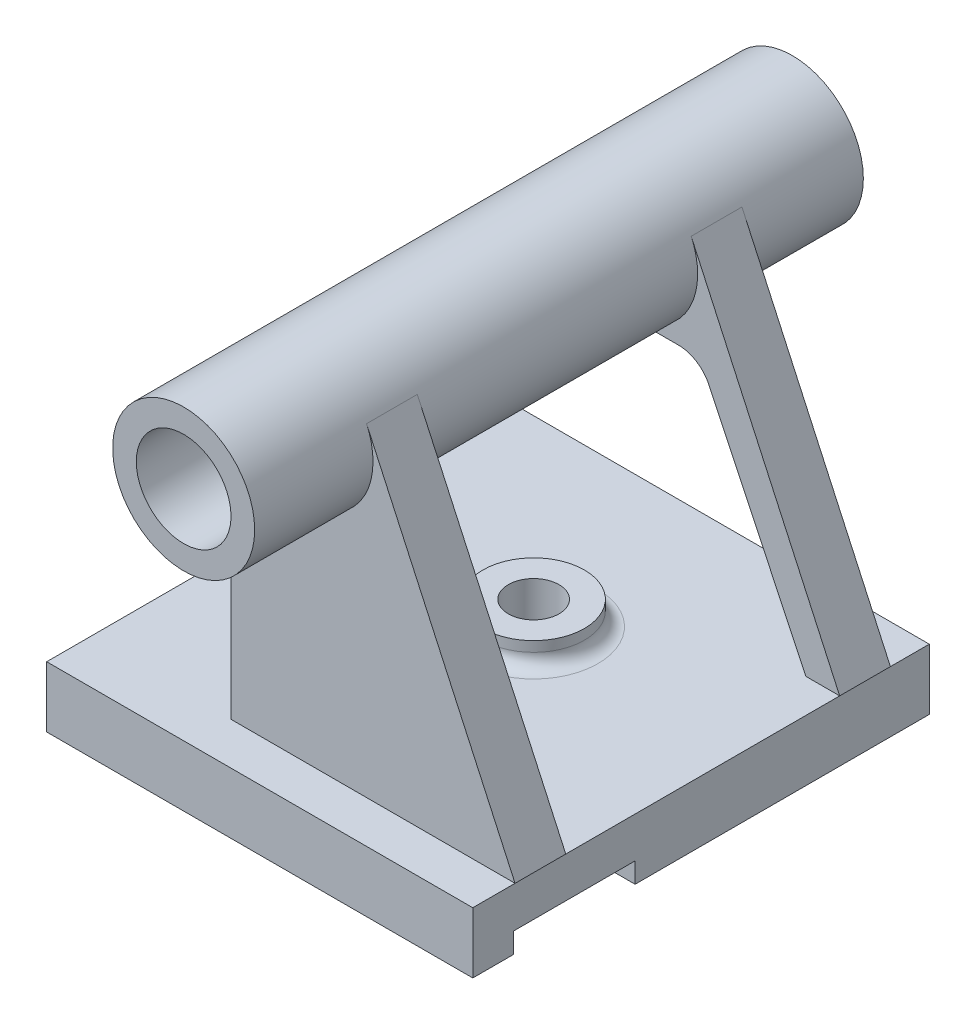
SolidWorks part; units mm, degrees
ref_plane "Front Plane" through (0, 0, 0) normal (0, 0, 1) x (1, 0, 0)
ref_plane "Top Plane" through (0, 0, 0) normal (0, 1, 0) x (1, 0, 0)
ref_plane "Right Plane" through (0, 0, 0) normal (1, 0, 0) x (0, 0, -1)
sketch "Sketch1" plane through (0, 0, 0) normal (0, 0, 1) x (1, 0, 0)
  circle A0 centre (0, 0) radius 21
  circle A1 centre (0, 0) radius 14
  dimension "D1" = 28
  dimension "D2" = 42
extrude "Boss-Extrude1" add sketch "Sketch1" along normal blind 180
ref_plane "Plane1" through (0, 0, 90) normal (0, 0, -1) x (-1, 0, 0)
sketch "Sketch3" plane through (0, 0, 90) normal (0, 0, -1) x (-1, 0, 0)
  line L0 (0, 0) -> (0, -96) construction
  line L2 (-63, -87) -> (63, -87)
  line L3 (-63, -87) -> (-63, -105)
  line L4 (-63, -105) -> (63, -105)
  line L5 (63, -87) -> (63, -105)
  line L6 (-63, -87) -> (63, -105) construction
  line L7 (-63, -105) -> (63, -87) construction
  dimension "D1" = 96
  dimension "D2" = 18
  dimension "D3" = 63
extrude "Boss-Extrude3" add sketch "Sketch3" along normal mid plane 135 separate body
sketch "Sketch4" plane through (63, 0, 0) normal (1, 0, 0) x (0, 0, -1)
  line L0 (-22.5, -105) -> (-157.5, -105) construction
  line L1 (-145.5, -105) -> (-109.5, -105)
  line L2 (-145.5, -105) -> (-145.5, -99)
  line L3 (-145.5, -99) -> (-109.5, -99)
  line L4 (-109.5, -105) -> (-109.5, -99)
  line L5 (-157.5, -87) -> (-157.5, -105) construction
  point P6 (0, 0)
  point P8 (-157.5, -105)
  dimension "D1" = 6
  dimension "D2" = 12
  dimension "D3" = 36
extrude "Cut-Extrude1" cut sketch "Sketch4" against normal blind 135
sketch "Sketch5" plane through (0, -87, 0) normal (0, 1, 0) x (1, 0, 0)
  line L0 (63, -76.5) -> (-63, -76.5) construction
  line L1 (63, -22.5) -> (63, -157.5) construction
  line L2 (-63, -22.5) -> (-63, -157.5) construction
  line L3 (0, -22.5) -> (0, -157.5) construction
  line L4 (-63, -22.5) -> (63, -22.5) construction
  line L5 (-63, -157.5) -> (63, -157.5) construction
  circle A0 centre (0, -76.5) radius 15
  circle A1 centre (0, -76.5) radius 7.5
  dimension "D2" = 15
  dimension "D3" = 30
  dimension "D1" = 81
extrude "Boss-Extrude4" add sketch "Sketch5" along normal blind 7
fillet "Fillet1" radius 4 1 edges at (0, -87, 61.5)
ref_plane "Plane2" through (0, 0, 145) normal (0, 0, 1) x (1, 0, 0)
sketch "Sketch6" plane through (0, 0, 145) normal (0, 0, 1) x (1, 0, 0)
  line L0 (-21, 0) -> (-21, -87)
  line L1 (-63, -87) -> (63, -87) construction
  line L2 (19.0885, 8.7538) -> (63, -87)
  line L3 (-21, -87) -> (63, -87)
  line L4 (63, -87) -> (63, -105) construction
  circle A0 centre (0, 0) radius 21 construction
  arc A1 (-21, 0) -> (19.0885, 8.7538) centre (0, 0) ccw
extrude "Boss-Extrude5" add sketch "Sketch6" against normal blind 15
ref_plane "Plane3" through (0, 0, 49) normal (0, 0, -1) x (-1, 0, 0)
sketch "Sketch8" plane through (0, 0, 49) normal (0, 0, -1) x (-1, 0, 0)
  line L0 (0, -21) -> (-15.3174, -21)
  line L1 (-24.3495, -26.708) -> (-53, -87)
  line L2 (63, -87) -> (-63, -87) construction
  line L3 (-19.0885, 8.7538) -> (-63, -87)
  line L4 (-63, -87) -> (-63, -105) construction
  line L5 (-63, -87) -> (-53, -87)
  arc A0 (-19.0885, 8.7538) -> (21, 0) centre (0, 0) ccw construction
  circle A1 centre (0, 0) radius 21 construction
  arc A2 (-15.3174, -21) -> (-24.3495, -26.708) centre (-15.3174, -31) ccw
  arc A3 (0, -21) -> (-19.0885, 8.7538) centre (0, 0) cw
  dimension "D1" = 10
  dimension "D2" = 10
  dimension "D3" = 10
extrude "Boss-Extrude6" add sketch "Sketch8" along normal blind 15
sketch "Sketch9" plane through (0, -87, 0) normal (0, 1, 0) x (1, 0, 0)
  circle A0 centre (0, -76.5) radius 7.5
  dimension "D1" = 15
extrude "Cut-Extrude2" cut sketch "Sketch9" against normal blind 49
